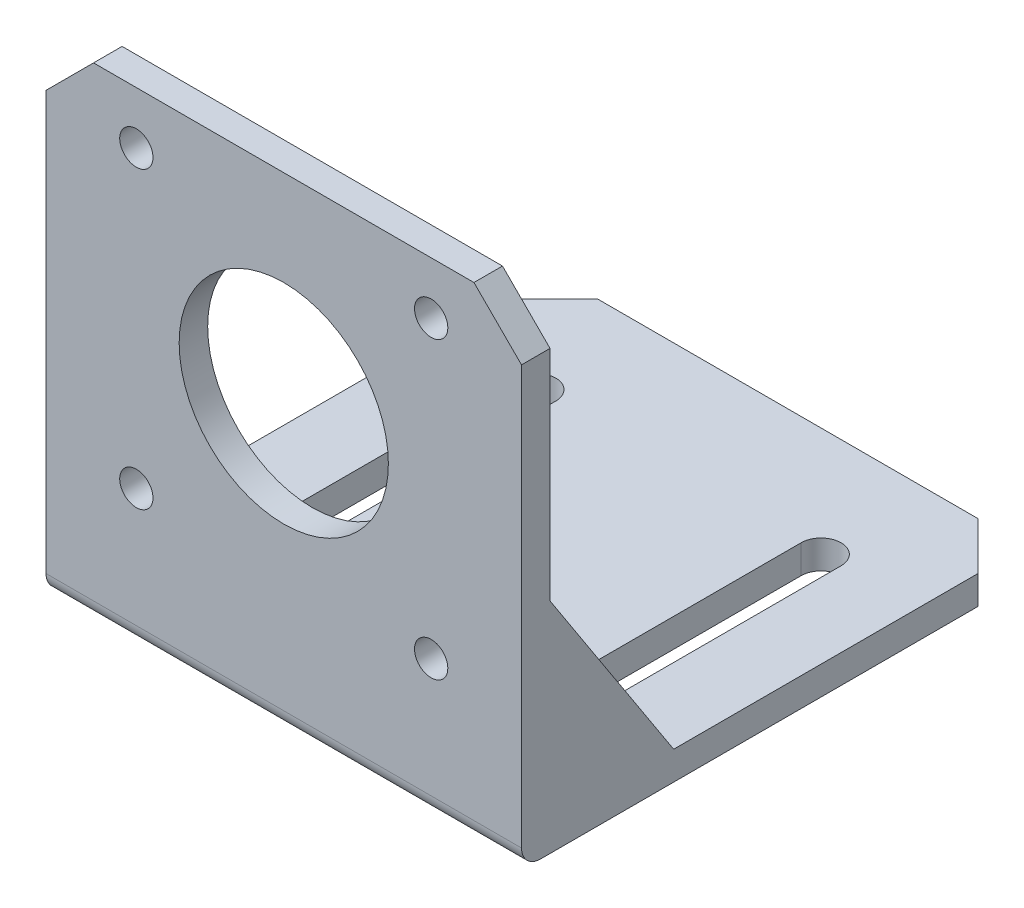
SolidWorks part; units mm, degrees
ref_plane "前视基准面" through (0, 0, 0) normal (0, 0, 1) x (1, 0, 0)
ref_plane "上视基准面" through (0, 0, 0) normal (0, 1, 0) x (1, 0, 0)
ref_plane "右视基准面" through (0, 0, 0) normal (1, 0, 0) x (0, 0, -1)
sketch "草图1" plane through (0, 0, 0) normal (1, 0, 0) x (0, 0, -1)
  line L0 (0, 2) -> (0, 51)
  line L1 (2, 0) -> (53, 0)
  line L2 (53, 0) -> (53, 3)
  line L3 (53, 3) -> (5, 3)
  line L4 (3, 5) -> (3, 51)
  line L5 (3, 51) -> (0, 51)
  arc A0 (5, 3) -> (3, 5) centre (5, 5) cw
  arc A1 (0, 2) -> (2, 0) centre (2, 2) ccw
  point P11 (0, 0)
  dimension "D1" = 2
  dimension "D2" = 2
extrude "凸台-拉伸1" add sketch "草图1" along normal blind 50
sketch "草图3" plane through (0, 0, 0) normal (1, 0, 0) x (0, 0, -1)
  line L0 (3, 5) -> (3, 23)
  line L1 (3, 5) -> (3, 51) construction
  line L2 (5, 3) -> (16, 3)
  line L3 (53, 3) -> (5, 3) construction
  line L4 (16, 3) -> (3, 23)
  arc A0 (3, 5) -> (5, 3) centre (5, 5) ccw
  dimension "D1" = 2
extrude "凸台-拉伸2" add sketch "草图3" along normal blind 3
ref_plane "基准面4" through (50, 0, 0) normal (1, 0, 0) x (0, 0, -1)
sketch "草图4" plane through (50, 0, 0) normal (1, 0, 0) x (0, 0, -1)
  line L0 (3, 23) -> (3, 5)
  line L1 (5, 3) -> (16, 3)
  line L2 (53, 3) -> (5, 3) construction
  line L3 (16, 3) -> (3, 23) construction
  line L4 (16, 3) -> (3, 23)
  arc A0 (3, 5) -> (5, 3) centre (5, 5) ccw
  dimension "D1" = 2
extrude "凸台-拉伸3" add sketch "草图4" against normal blind 3
sketch "草图5" plane through (0, 0, 0) normal (0, 0, 1) x (1, 0, 0)
  circle A0 centre (25, 30) radius 11
  circle A1 centre (9.5, 45.5) radius 1.75
  circle A2 centre (40.5, 45.5) radius 1.75
  circle A3 centre (9.5, 14.5) radius 1.75
  circle A4 centre (40.5, 14.5) radius 1.75
extrude "切除-拉伸1" cut sketch "草图5" against normal blind 3
sketch "草图6" plane through (0, 0, 0) normal (0, 1, 0) x (1, 0, 0)
  line L0 (7.9, 41.5) -> (7.9, 11.5)
  line L2 (12.1, 11.5) -> (12.1, 41.5)
  line L3 (37.9, 41.5) -> (37.9, 11.5)
  line L8 (42.1, 41.5) -> (42.1, 11.5)
  arc A0 (12.1, 41.5) -> (7.9, 41.5) centre (10, 41.5) ccw
  arc A1 (42.1, 41.5) -> (37.9, 41.5) centre (40, 41.5) ccw
  arc A2 (7.9, 11.5) -> (12.1, 11.5) centre (10, 11.5) ccw
  arc A3 (37.9, 11.5) -> (42.1, 11.5) centre (40, 11.5) ccw
extrude "切除-拉伸2" cut sketch "草图6" along normal blind 11
chamfer "倒角1" distance 5 angle 45 4 edges at (0, 1.5, -53) (50, 1.5, -53) (0, 51, -1.5) (50, 51, -1.5)
